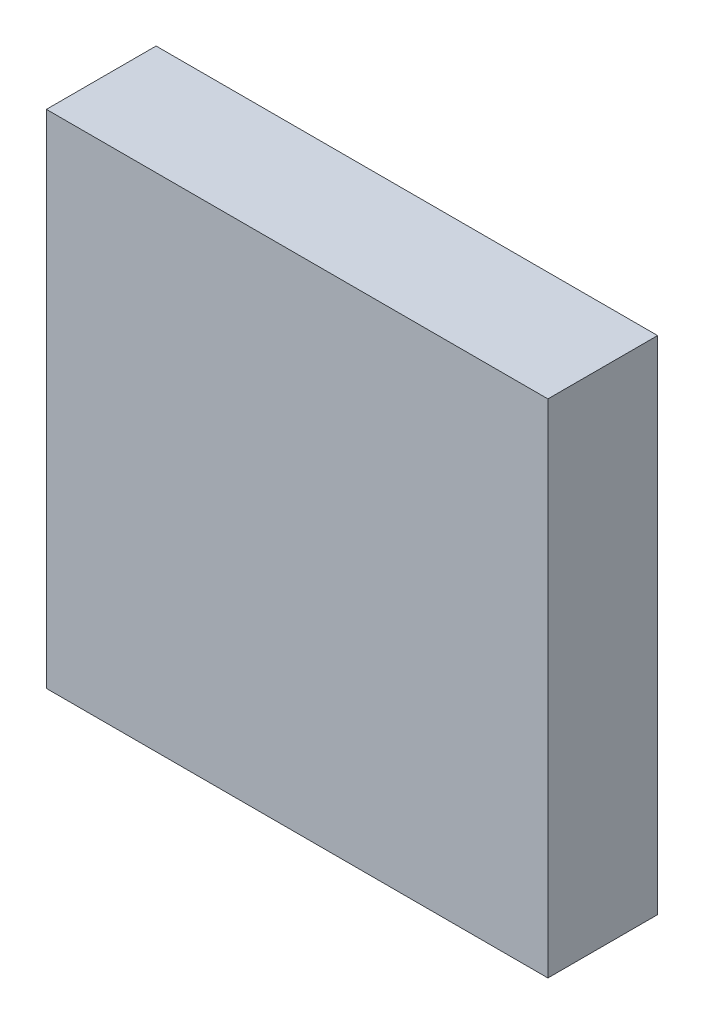
SolidWorks part; units mm, degrees
ref_plane "Front Plane" through (0, 0, 0) normal (0, 0, 1) x (1, 0, 0)
ref_plane "Top Plane" through (0, 0, 0) normal (0, 1, 0) x (1, 0, 0)
ref_plane "Right Plane" through (0, 0, 0) normal (1, 0, 0) x (0, 0, -1)
sketch "Sketch1" plane through (0, 0, 0) normal (0, 0, 1) x (1, 0, 0)
  line L1 (-16, 16) -> (16, 16)
  line L2 (-16, 16) -> (-16, -16)
  line L3 (-16, -16) -> (16, -16)
  line L4 (16, 16) -> (16, -16)
  line L5 (-16, 16) -> (16, -16) construction
  line L6 (-16, -16) -> (16, 16) construction
  point P0 (0, 0)
extrude "Boss-Extrude1" add sketch "Sketch1" along normal blind 7
